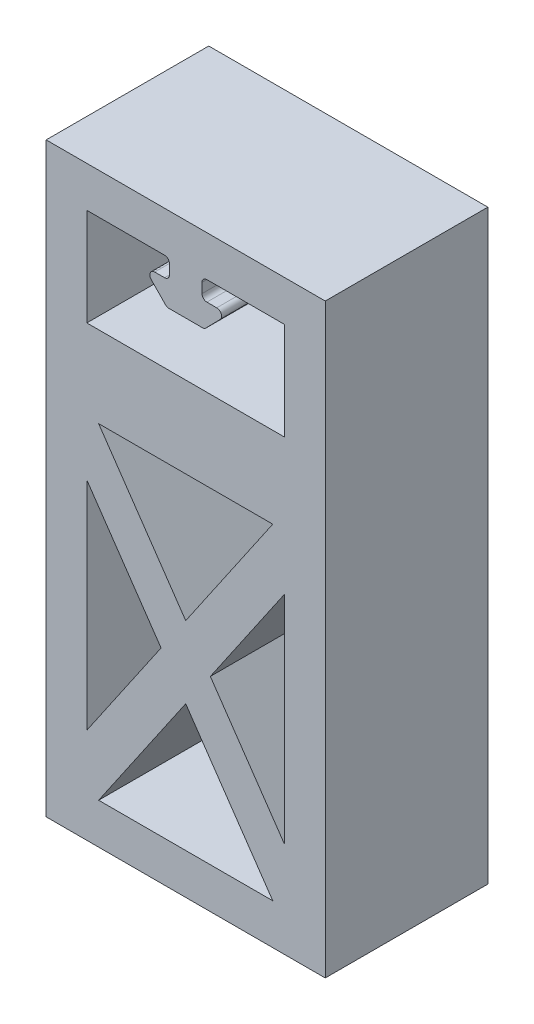
SolidWorks part; units mm, degrees
ref_plane "Front Plane" through (0, 0, 0) normal (0, 0, 1) x (1, 0, 0)
ref_plane "Top Plane" through (0, 0, 0) normal (0, 1, 0) x (1, 0, 0)
ref_plane "Right Plane" through (0, 0, 0) normal (1, 0, 0) x (0, 0, -1)
sketch "Sketch1" plane through (0, 0, 0) normal (0, 0, 1) x (1, 0, 0)
  line L0 (-21.8, -13.97) -> (21.8, -13.97) construction
  line L6 (-21.8, -13.97) -> (-21.8, 13.97)
  line L7 (-21.8, 13.97) -> (21.8, 13.97)
  line L8 (21.8, -13.97) -> (21.8, 13.97)
  line L9 (-21.8, 13.97) -> (21.8, -13.97) construction
  line L10 (-21.8, -13.97) -> (21.8, 13.97) construction
  line L11 (-15.45, 7.62) -> (-2.54, 7.62)
  line L12 (-15.45, 7.62) -> (-15.45, -7.62)
  line L13 (-15.45, -7.62) -> (15.45, -7.62)
  line L14 (15.45, 7.62) -> (15.45, -7.62)
  line L15 (-15.45, 7.62) -> (15.45, -7.62) construction
  line L16 (-15.45, -7.62) -> (15.45, 7.62) construction
  line L17 (-21.8, -13.97) -> (-21.8, -77.62)
  line L18 (-21.8, -77.62) -> (21.8, -77.62)
  line L19 (21.8, -13.97) -> (21.8, -77.62)
  line L20 (-21.8, -13.97) -> (21.8, -77.62) construction
  line L21 (-21.8, -77.62) -> (21.8, -13.97) construction
  line L22 (-13.6018, -20.32) -> (0, -40.1768)
  line L23 (15.45, -28.8583) -> (3.8485, -45.795)
  line L24 (13.6018, -20.32) -> (0, -40.1768)
  line L25 (0, 13.97) -> (0, -13.97) construction
  line L26 (-3.8485, -45.795) -> (-15.45, -62.7317)
  line L27 (3.8485, -45.795) -> (15.45, -62.7317)
  line L28 (0, -51.4132) -> (-13.6018, -71.27)
  line L29 (0, -51.4132) -> (13.6018, -71.27)
  line L30 (-13.6018, -20.32) -> (13.6018, -20.32)
  line L31 (15.45, -28.8583) -> (15.45, -62.7317)
  line L32 (13.6018, -71.27) -> (-13.6018, -71.27)
  line L33 (-15.45, -62.7317) -> (-15.45, -28.8583)
  line L34 (-15.45, -28.8583) -> (-3.8485, -45.795)
  line L35 (-2.54, 7.62) -> (-2.54, 4.572)
  line L36 (-2.54, 4.572) -> (-6.6548, 4.572)
  line L37 (-6.6548, 4.572) -> (-2.9337, 0.762)
  line L38 (-2.9337, 0.762) -> (2.9337, 0.762)
  line L39 (6.6548, 4.572) -> (2.9337, 0.762)
  line L40 (2.54, 4.572) -> (6.6548, 4.572)
  line L41 (2.54, 7.62) -> (2.54, 4.572)
  line L42 (2.54, 7.62) -> (15.45, 7.62)
  point P0 (0, 0)
  point P8 (0, 0)
  point P9 (0, 0)
  point P31 (0, 0.762)
  dimension "D8" = 6.35
  dimension "D1" = 6.35
  dimension "D2" = 2.54
  dimension "D3" = 6.35
  dimension "D4" = 30.9
  dimension "D5" = 70
  dimension "D6" = 3.175
  dimension "D7" = 3.175
  dimension "D9" = 3.048
  dimension "D10" = 6.35
  dimension "D11" = 6.6548
  dimension "D12" = 3.175
  dimension "D13" = 3.175
  dimension "D14" = 3.175
  dimension "D15" = 6.858
  dimension "D16" = 15.24
extrude "Boss-Extrude1" add sketch "Sketch1" along normal blind 25.4
fillet "Fillet1" radius 0.762 8 edges at (-2.54, 7.62, 12.7) (2.54, 7.62, 12.7) (-2.9337, 0.762, 12.7) (-6.6548, 4.572, 12.7) (-2.54, 4.572, 12.7) (2.9337, 0.762, 12.7) (6.6548, 4.572, 12.7) (2.54, 4.572, 12.7)
